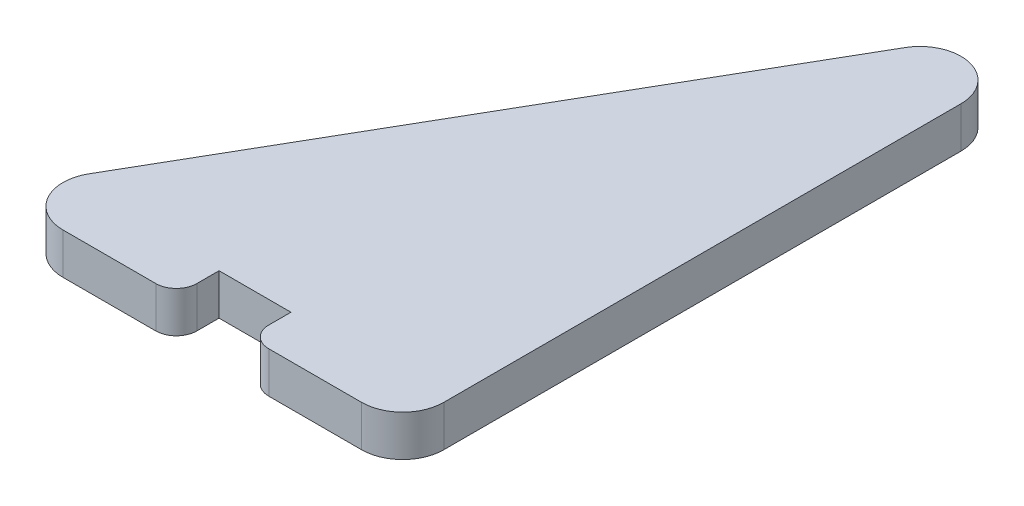
SolidWorks part; units mm, degrees
material "Acrylic (Medium-high impact)"
ref_plane "Front Plane" through (0, 0, 0) normal (0, 0, 1) x (1, 0, 0)
ref_plane "Top Plane" through (0, 0, 0) normal (0, 1, 0) x (1, 0, 0)
ref_plane "Right Plane" through (0, 0, 0) normal (1, 0, 0) x (0, 0, -1)
sketch "Sketch1" plane through (0, 0, 0) normal (0, 1, 0) x (1, 0, 0)
  line L10 (0, 6.35) -> (0, 86.2867)
  line L11 (-11.8493, 89.4617) -> (-58.0007, 9.525)
  line L12 (-52.5015, 0) -> (-6.35, 0)
  arc A6 (-58.0007, 9.525) -> (-52.5015, 0) centre (-52.5015, 6.35) ccw
  arc A7 (0, 6.35) -> (-6.35, 0) centre (-6.35, 6.35) cw
  arc A8 (0, 86.2867) -> (-11.8493, 89.4617) centre (-6.35, 86.2867) ccw
  point P3 (-63.5, 0)
  point P4 (0, 0)
  point P7 (0, 0)
  point P10 (0, 0)
  point P13 (0, 109.9852)
  dimension "D2" = 6.35
  dimension "D1" = 63.5
  dimension "D3" = 60
extrude "Boss-Extrude1" add sketch "Sketch1" along normal blind 6.35
sketch "Sketch3" plane through (0, 0, 0) normal (0, -1, 0) x (1, 0, 0)
  line L0 (-23.8695, -6.604) -> (-34.982, -6.604) construction
  line L1 (-23.8695, -6.604) -> (-34.982, -6.604)
  line L2 (-34.982, -6.604) -> (-34.982, -3.175) construction
  line L3 (-23.8695, -3.175) -> (-23.8695, -6.604) construction
  line L4 (-34.982, -6.604) -> (-34.982, -3.175)
  line L5 (-23.8695, -3.175) -> (-23.8695, -6.604)
  line L6 (-20.6945, 0) -> (-38.157, 0)
  arc A0 (-34.982, -3.175) -> (-38.157, 0) centre (-38.157, -3.175) ccw construction
  arc A1 (-20.6945, 0) -> (-23.8695, -3.175) centre (-20.6945, -3.175) ccw construction
  arc A2 (-34.982, -3.175) -> (-38.157, 0) centre (-38.157, -3.175) ccw
  arc A3 (-20.6945, 0) -> (-23.8695, -3.175) centre (-20.6945, -3.175) ccw
extrude "Cut-Extrude1" cut sketch "Sketch3" against normal through all
